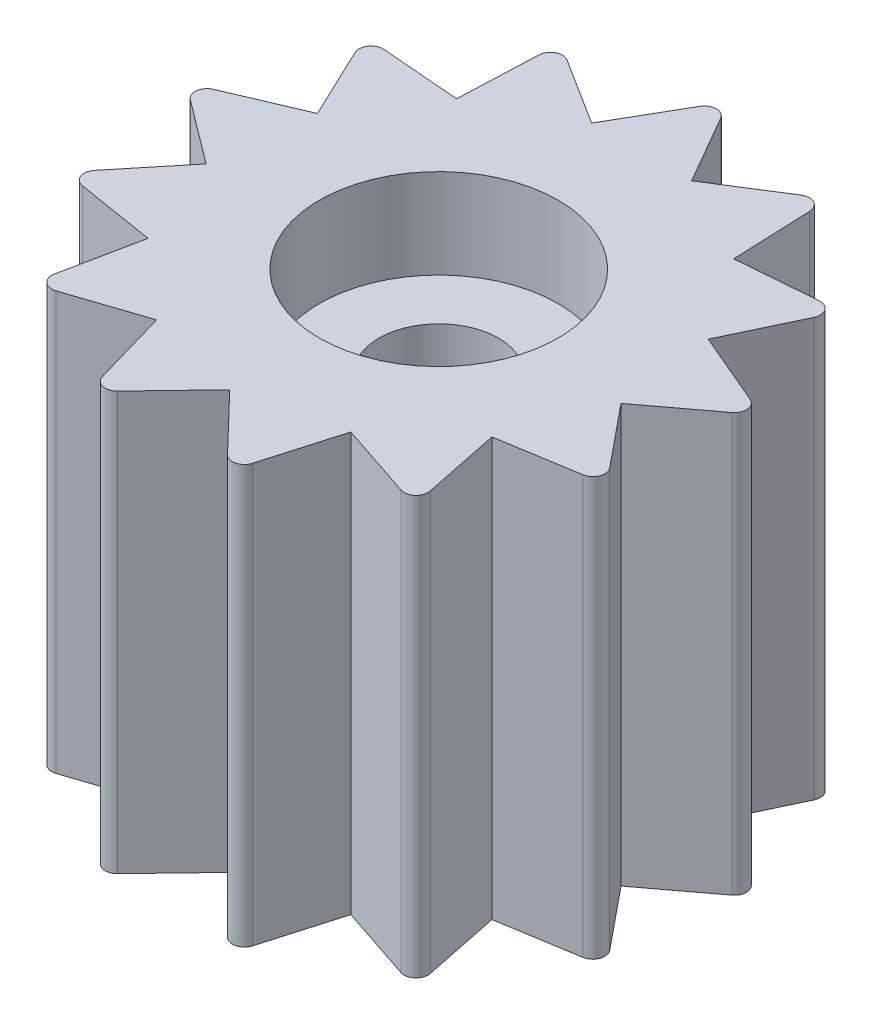
SolidWorks part; units mm, degrees
ref_plane "Front" through (0, 0, 0) normal (0, 0, 1) x (1, 0, 0)
ref_plane "Top" through (0, 0, 0) normal (0, 1, 0) x (1, 0, 0)
ref_plane "Right" through (0, 0, 0) normal (1, 0, 0) x (0, 0, -1)
sketch "Sketch1" plane through (0, 0, 0) normal (0, 1, 0) x (1, 0, 0)
  line L0 (2.3209, 2.6198) -> (3.9907, 2.7546)
  line L1 (3.9907, 2.7546) -> (3.2726, 1.2411)
  line L2 (3.2726, 1.2411) -> (4.8137, 0.5845)
  line L3 (4.8137, 0.5845) -> (3.4745, -0.4219)
  line L4 (3.4745, -0.4219) -> (4.534, -1.7195)
  line L5 (4.534, -1.7195) -> (2.8804, -1.9882)
  line L6 (2.8804, -1.9882) -> (3.2155, -3.6296)
  line L7 (3.2155, -3.6296) -> (1.6265, -3.0991)
  line L8 (1.6265, -3.0991) -> (1.1605, -4.7082)
  line L9 (1.1605, -4.7082) -> (0, -3.5)
  line L10 (0, -3.5) -> (-1.1605, -4.7082)
  line L11 (-1.1605, -4.7082) -> (-1.6265, -3.0991)
  line L12 (-1.6265, -3.0991) -> (-3.2155, -3.6296)
  line L13 (-3.2155, -3.6296) -> (-2.8804, -1.9882)
  line L14 (-2.8804, -1.9882) -> (-4.534, -1.7195)
  line L15 (-4.534, -1.7195) -> (-3.4745, -0.4219)
  line L16 (-3.4745, -0.4219) -> (-4.8137, 0.5845)
  line L17 (-4.8137, 0.5845) -> (-3.2726, 1.2411)
  line L18 (-3.2726, 1.2411) -> (-3.9907, 2.7546)
  line L19 (-3.9907, 2.7546) -> (-2.3209, 2.6198)
  line L20 (-2.3209, 2.6198) -> (-2.2535, 4.2936)
  line L21 (-2.2535, 4.2936) -> (-0.8376, 3.3983)
  line L22 (-0.8376, 3.3983) -> (0, 4.8491)
  line L23 (0, 4.8491) -> (0.8376, 3.3983)
  line L24 (0.8376, 3.3983) -> (2.2535, 4.2936)
  line L25 (2.2535, 4.2936) -> (2.3209, 2.6198)
  line L26 (-0.8376, 3.3983) -> (0.8376, 3.3983) construction
  circle A0 centre (0, 0) radius 3.5 construction
  circle A1 centre (0, 0) radius 1
  point P44 (0, 0)
  dimension "D2" = 7
  dimension "D4" = 2
  dimension "D3" = 60
  dimension "D5" = 1.6752
  dimension "D6" = 1.4508
  dimension "D1" = 13
extrude "Boss-Extrude1" add sketch "Sketch1" along normal blind 7
sketch "Sketch2" plane through (0, 0, 0) normal (0, -1, 0) x (1, 0, 0)
  line L0 (0, 2.25) -> (-0.3534, 1.6629)
  line L1 (-0.3534, 1.6629) -> (-0.9152, 2.0555)
  line L2 (-0.9152, 2.0555) -> (-0.9992, 1.3753)
  line L3 (-0.9992, 1.3753) -> (-1.6721, 1.5055)
  line L4 (-1.6721, 1.5055) -> (-1.4722, 0.85)
  line L5 (-1.4722, 0.85) -> (-2.1399, 0.6953)
  line L6 (-2.1399, 0.6953) -> (-1.6907, 0.1777)
  line L7 (-1.6907, 0.1777) -> (-2.2377, -0.2352)
  line L8 (-2.2377, -0.2352) -> (-1.6168, -0.5253)
  line L9 (-1.6168, -0.5253) -> (-1.9486, -1.125)
  line L10 (-1.9486, -1.125) -> (-1.2633, -1.1375)
  line L11 (-1.2633, -1.1375) -> (-1.3225, -1.8203)
  line L12 (-1.3225, -1.8203) -> (-0.6915, -1.553)
  line L13 (-0.6915, -1.553) -> (-0.4678, -2.2008)
  line L14 (-0.4678, -2.2008) -> (0, -1.7)
  line L15 (0, -1.7) -> (0.4678, -2.2008)
  line L16 (0.4678, -2.2008) -> (0.6915, -1.553)
  line L17 (0.6915, -1.553) -> (1.3225, -1.8203)
  line L18 (1.3225, -1.8203) -> (1.2633, -1.1375)
  line L19 (1.2633, -1.1375) -> (1.9486, -1.125)
  line L20 (1.9486, -1.125) -> (1.6168, -0.5253)
  line L21 (1.6168, -0.5253) -> (2.2377, -0.2352)
  line L22 (2.2377, -0.2352) -> (1.6907, 0.1777)
  line L23 (1.6907, 0.1777) -> (2.1399, 0.6953)
  line L24 (2.1399, 0.6953) -> (1.4722, 0.85)
  line L25 (1.4722, 0.85) -> (1.6721, 1.5055)
  line L26 (1.6721, 1.5055) -> (0.9992, 1.3753)
  line L27 (0.9992, 1.3753) -> (0.9152, 2.0555)
  line L28 (0.9152, 2.0555) -> (0.3534, 1.6629)
  line L29 (0.3534, 1.6629) -> (0, 2.25)
  circle A0 centre (0, 0) radius 2.25 construction
  circle A1 centre (0, 0) radius 1.7 construction
  point P31 (0.3117, -1.8211)
  point P33 (0.1141, 1.6687)
  point P34 (0.6928, 2.113)
  point P35 (0.7891, 1.519)
  point P36 (1.1344, 1.8928)
  point P37 (0, 0)
  point P38 (-1.1586, 1.0939)
  point P39 (1.5132, 0.7286)
  point P40 (2.2851, 0.4801)
  point P41 (-1.7165, 1.3204)
  point P42 (1.3188, -1.6827)
  point P43 (1.8613, -1.0909)
  point P44 (1.0063, 0.8747)
  point P45 (-0.8103, -1.9723)
  point P46 (1.4376, 1.5798)
  point P47 (1.8629, 1.0528)
  point P48 (1.005, -1.7667)
  point P49 (0.8872, -0.9321)
  point P50 (1.66, -1.1163)
  point P52 (1.2834, -0.4189)
  point P53 (1.9341, -0.5093)
  point P54 (1.9953, -0.1363)
  point P55 (1.3055, 0.1958)
  point P56 (1.8985, 0.6291)
  point P57 (1.1907, 0.6291)
  point P58 (1.508, 1.3245)
  dimension "D1" = 3.4
  dimension "D2" = 4.5
extrude "Cut-Extrude1" cut sketch "Sketch2" against normal blind 3
fillet "Fillet1" radius 0.2 13 edges at (-4.8137, 3.5, -0.5845) (-4.534, 3.5, 1.7195) (-3.2155, 3.5, 3.6296) (-1.1605, 3.5, 4.7082) (1.1605, 3.5, 4.7082) (3.2155, 3.5, 3.6296) (4.534, 3.5, 1.7195) (4.8137, 3.5, -0.5845) (3.9907, 3.5, -2.7546) (2.2535, 3.5, -4.2936) (0, 3.5, -4.8491) (-2.2535, 3.5, -4.2936) (-3.9907, 3.5, -2.7546)
sketch "Sketch3" plane through (0, 7, 0) normal (0, 1, 0) x (1, 0, 0)
  circle A0 centre (0, 0) radius 2
  dimension "D1" = 4
extrude "Cut-Extrude2" cut sketch "Sketch3" against normal blind 1.5
